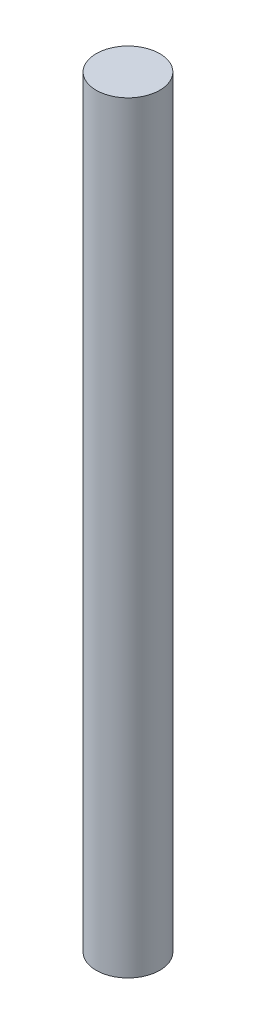
SolidWorks part; units mm, degrees
ref_plane "Front Plane" through (0, 0, 0) normal (0, 0, 1) x (1, 0, 0)
ref_plane "Top Plane" through (0, 0, 0) normal (0, 1, 0) x (1, 0, 0)
ref_plane "Right Plane" through (0, 0, 0) normal (1, 0, 0) x (0, 0, -1)
sketch "Sketch2" plane through (0, 0, 0) normal (0, 1, 0) x (1, 0, 0)
  circle A0 centre (0, 0) radius 2.5
  dimension "D1" = 5
extrude "Boss-Extrude1" add sketch "Sketch2" along normal blind 60
